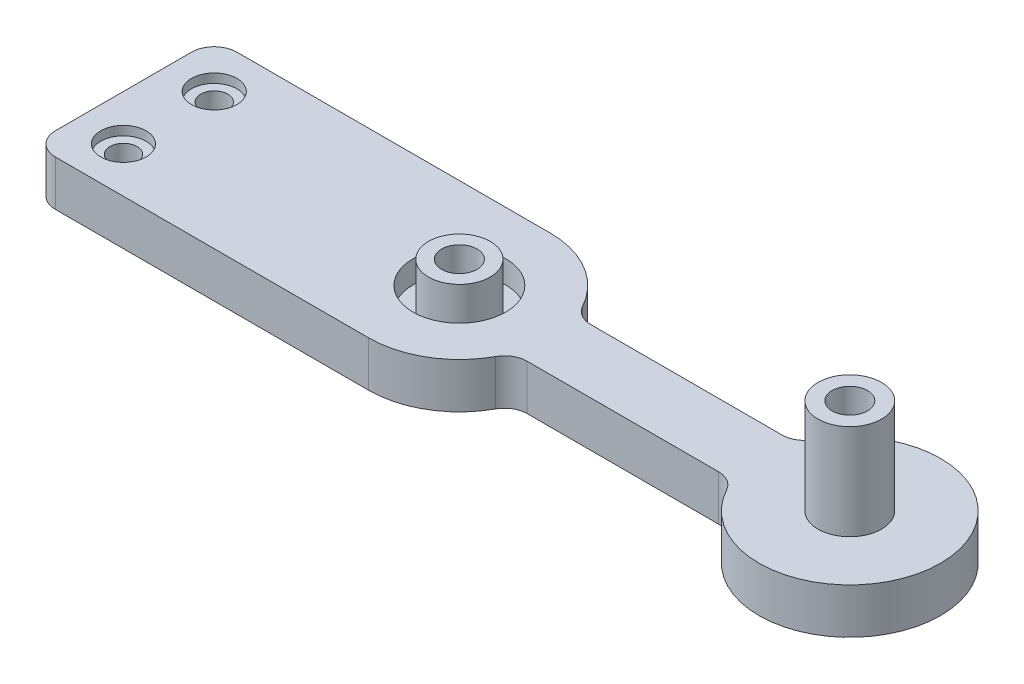
SolidWorks part; units mm, degrees
material "6061 Alloy"
ref_plane "Front Plane" through (0, 0, 0) normal (0, 0, 1) x (1, 0, 0)
ref_plane "Top Plane" through (0, 0, 0) normal (0, 1, 0) x (1, 0, 0)
ref_plane "Right Plane" through (0, 0, 0) normal (1, 0, 0) x (0, 0, -1)
sketch "Sketch1" plane through (0, 0, 0) normal (0, 1, 0) x (1, 0, 0)
  line L0 (0, 12.7) -> (-43.815, 12.7)
  line L1 (-46.99, 9.525) -> (-46.99, -9.525)
  line L2 (-43.815, -12.7) -> (0, -12.7)
  line L3 (13.9266, 4.445) -> (40.6834, 4.445)
  line L4 (13.9266, -4.445) -> (40.6834, -4.445)
  circle A0 centre (0, 0) radius 2.4765
  arc A1 (11.1413, 6.096) -> (0, 12.7) centre (0, 0) ccw
  circle A2 centre (54.61, 0) radius 2.4765
  arc A3 (43.4687, -6.096) -> (43.4687, 6.096) centre (54.61, 0) ccw
  arc A4 (-46.99, -9.525) -> (-43.815, -12.7) centre (-43.815, -9.525) ccw
  arc A5 (-43.815, 12.7) -> (-46.99, 9.525) centre (-43.815, 9.525) ccw
  arc A6 (40.6834, 4.445) -> (43.4687, 6.096) centre (40.6834, 7.62) ccw
  arc A7 (40.6834, -4.445) -> (43.4687, -6.096) centre (40.6834, -7.62) cw
  arc A8 (13.9266, -4.445) -> (11.1413, -6.096) centre (13.9266, -7.62) ccw
  arc A9 (13.9266, 4.445) -> (11.1413, 6.096) centre (13.9266, 7.62) cw
  arc A10 (0, -12.7) -> (11.1413, -6.096) centre (0, 0) ccw
  point P15 (-40.64, -6.35)
  point P29 (-40.64, 6.35)
  dimension "D1" = 4.953
  dimension "D2" = 25.4
  dimension "D4" = 25.4
  dimension "D5" = 4.953
  dimension "D9" = 3.175
  dimension "D3" = 46.99
  dimension "D6" = 54.61
  dimension "D7" = 8.89
  dimension "D8" = 4.445
  dimension "D10" = 12.7
  dimension "D11" = 6.35
  dimension "D12" = 6.35
extrude "Boss-Extrude1" add sketch "Sketch1" along normal blind 6.35
sketch "Sketch2" plane through (0, 6.35, 0) normal (0, 1, 0) x (1, 0, 0)
  circle A0 centre (0, 0) radius 6.477
  dimension "D1" = 12.954
extrude "Cut-Extrude1" cut sketch "Sketch2" against normal blind 3.175
sketch "Sketch3" plane through (0, 3.175, 0) normal (0, 1, 0) x (1, 0, 0)
  circle A0 centre (0, 0) radius 4.318
  circle A1 centre (0, 0) radius 2.4765 construction
  circle A2 centre (0, 0) radius 2.4765
  dimension "D1" = 8.636
extrude "Boss-Extrude2" add sketch "Sketch3" along normal blind 6.35
sketch "Sketch4" plane through (0, 6.35, 0) normal (0, 1, 0) x (1, 0, 0)
  circle A0 centre (54.61, 0) radius 4.445
  circle A1 centre (54.61, 0) radius 2.4765 construction
  circle A2 centre (54.61, 0) radius 2.4765
  dimension "D1" = 8.89
extrude "Boss-Extrude3" add sketch "Sketch4" along normal blind 13.335
sketch "Sketch5" plane through (0, 6.35, 0) normal (0, 1, 0) x (1, 0, 0)
  point P0 (-40.64, -6.35)
  point P2 (-40.64, 6.35)
sketch "Sketch6" plane through (0, 6.35, 0) normal (0, 1, 0) x (1, 0, 0)
  circle A0 centre (-40.64, 6.35) radius 3.175
  circle A1 centre (-40.64, -6.35) radius 3.175
  dimension "D1" = 6.35
extrude "Cut-Extrude2" cut sketch "Sketch6" against normal blind 1.27
sketch "Sketch7" plane through (0, 5.08, 0) normal (0, 1, 0) x (1, 0, 0)
  point P0 (-40.64, 6.35)
  point P1 (-40.64, -6.35)
hole_wizard "#10-24 Tapped Hole1" positions "3DSketch1" profile "Sketch8" tap size "#10-24" standard "ANSI Inch" end condition up to next
sketch3d "3DSketch1"
  line L0 (-40.64, 5.08, -6.35) -> (-40.64, 6.35, -6.35) construction
  line L1 (-40.64, 5.08, 6.35) -> (-40.64, 6.35, 6.35) construction
  point P0 (-40.64, 6.35, -6.35)
  point P4 (-40.64, 6.35, 6.35)
sketch "Sketch8" plane through (-40.64, 6.35, -6.35) normal (1, 0, 0) x (0, 0, 1)
  line L0 (0, 0) -> (0, 6.35)
  line L1 (0, 6.35) -> (1.8986, 6.35)
  line L2 (1.8986, 6.35) -> (1.8986, 0)
  line L5 (1.8986, 0) -> (0, 0)
  line L11 (0, -6.35) -> (0, 107.95) construction
  dimension "Thru Tap Drill Dia." = 3.7973
  dimension "Thru Tap Drill Depth" = 6.35
cosmetic thread "Hole Thread1" parameters "D2"=4.826
cosmetic thread "Hole Thread2" parameters "D2"=4.826
